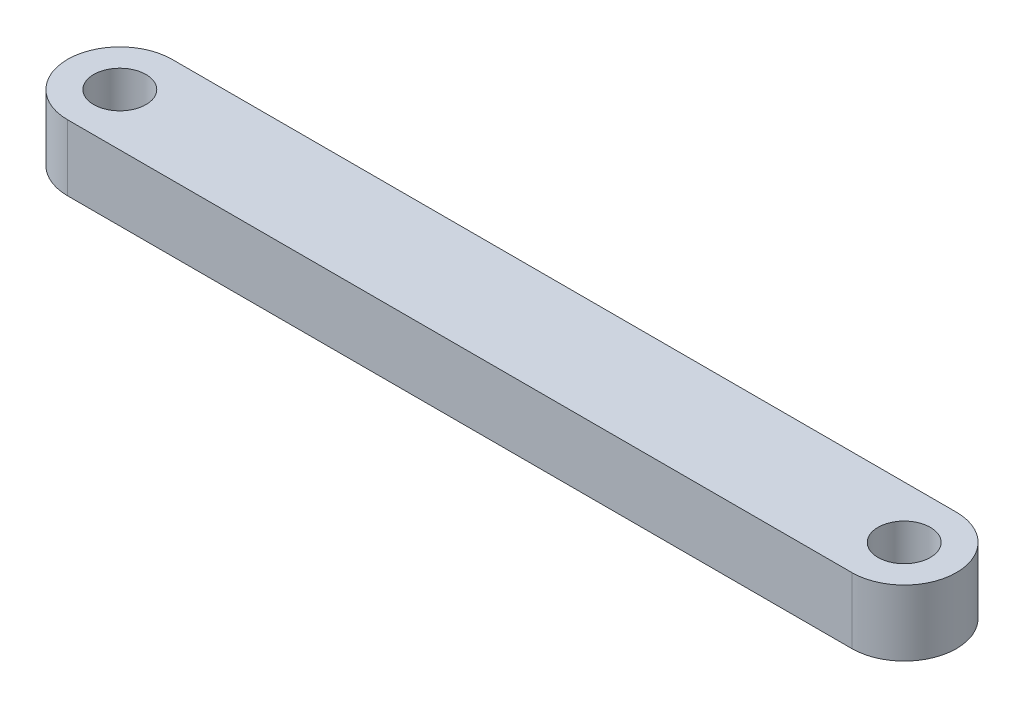
SolidWorks part; units mm, degrees
ref_plane "Front Plane" through (0, 0, 0) normal (0, 0, 1) x (1, 0, 0)
ref_plane "Top Plane" through (0, 0, 0) normal (0, 1, 0) x (1, 0, 0)
ref_plane "Right Plane" through (0, 0, 0) normal (1, 0, 0) x (0, 0, -1)
sketch "Sketch1" plane through (0, 0, 0) normal (0, 1, 0) x (1, 0, 0)
  line L1 (-31.75, -2.54) -> (6.35, -2.54)
  line L3 (-31.75, 2.54) -> (6.35, 2.54)
  arc A0 (-31.75, 2.54) -> (-31.75, -2.54) centre (-31.75, 0) ccw
  arc A1 (6.35, -2.54) -> (6.35, 2.54) centre (6.35, 0) ccw
  circle A2 centre (-31.75, 0) radius 1.27
  circle A3 centre (6.35, 0) radius 1.27
  point P0 (0, 0)
  dimension "D3" = 2.54
  dimension "D1" = 38.1
  dimension "D2" = 5.08
extrude "Boss-Extrude1" add sketch "Sketch1" along normal blind 3.2004
